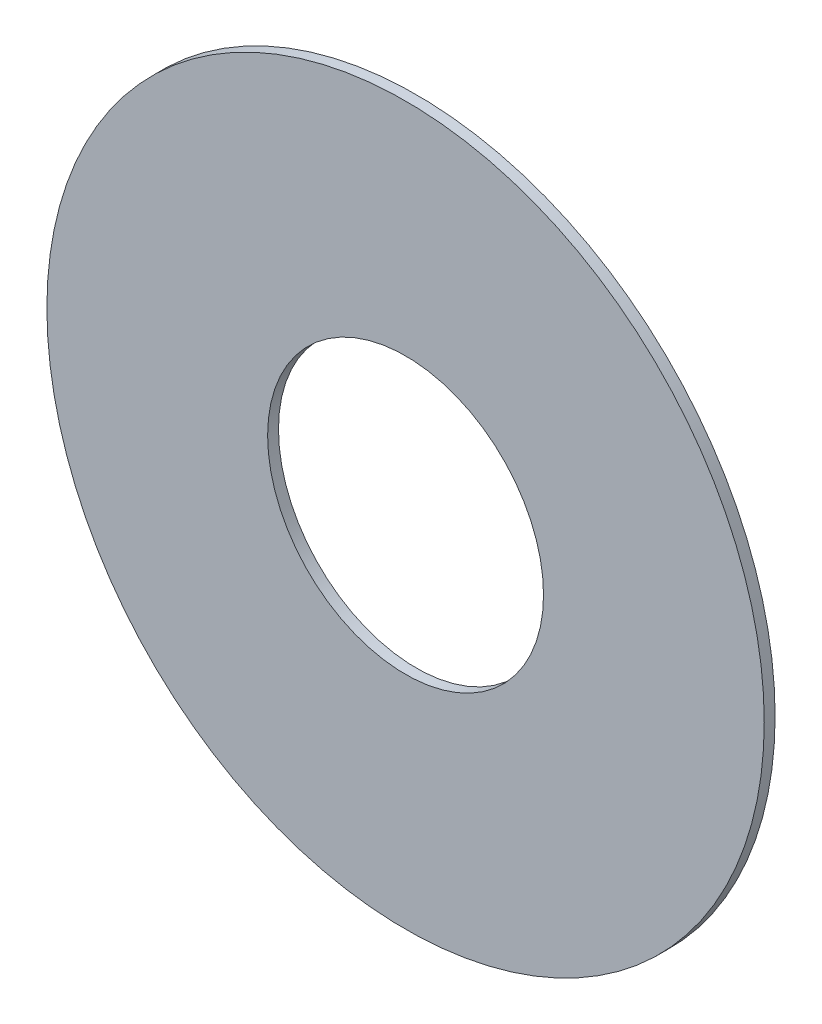
SolidWorks part; units mm, degrees
ref_plane "Front Plane" through (0, 0, 0) normal (0, 0, 1) x (1, 0, 0)
ref_plane "Top Plane" through (0, 0, 0) normal (0, 1, 0) x (1, 0, 0)
ref_plane "Right Plane" through (0, 0, 0) normal (1, 0, 0) x (0, 0, -1)
sketch "Sketch1" plane through (0, 0, 0) normal (0, 0, 1) x (1, 0, 0)
  circle A0 centre (0, 0) radius 63.5
  circle A1 centre (0, 0) radius 165.1
  dimension "D1" = 330.2
  dimension "D2" = 127
extrude "Boss-Extrude1" add sketch "Sketch1" along normal blind 5
